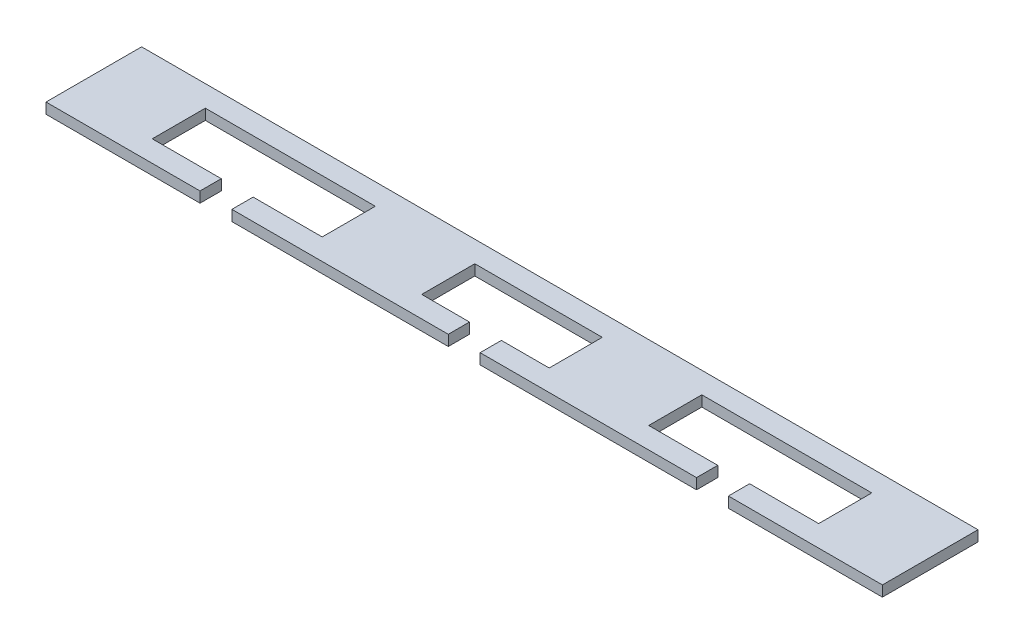
SolidWorks part; units mm, degrees
ref_plane "Front Plane" through (0, 0, 0) normal (0, 0, 1) x (1, 0, 0)
ref_plane "Top Plane" through (0, 0, 0) normal (0, 1, 0) x (1, 0, 0)
ref_plane "Right Plane" through (0, 0, 0) normal (1, 0, 0) x (0, 0, -1)
sketch "Sketch1" plane through (0, 0, 0) normal (0, 1, 0) x (1, 0, 0)
  line L0 (0, 57.15) -> (1000.0005, 57.15) construction
  line L2 (0, 0) -> (0, 114.3)
  line L3 (0, 114.3) -> (1000.0005, 114.3)
  line L4 (1000.0005, 0) -> (1000.0005, 114.3)
  line L9 (101.6, 25.4) -> (184.15, 25.4)
  line L10 (101.6, 25.4) -> (101.6, 88.9)
  line L12 (304.8, 25.4) -> (304.8, 88.9)
  line L17 (0, -31.5189) -> (406.4, -31.5189) construction
  line L18 (0, -31.5189) -> (0, -107.7189) construction
  line L19 (0, -107.7189) -> (406.4, -107.7189) construction
  line L20 (406.4, -31.5189) -> (406.4, -107.7189) construction
  line L21 (593.6005, -31.5189) -> (1000.0005, -31.5189) construction
  line L22 (593.6005, -31.5189) -> (593.6005, -107.7189) construction
  line L23 (593.6005, -107.7189) -> (1000.0005, -107.7189) construction
  line L24 (1000.0005, -31.5189) -> (1000.0005, -107.7189) construction
  line L25 (203.2, -31.5189) -> (203.2, -107.7189) construction
  line L26 (796.8005, -107.7189) -> (796.8005, -31.5189) construction
  line L27 (203.2, -31.5189) -> (203.2, 114.3) construction
  line L28 (796.8005, -31.5189) -> (796.8005, 114.3) construction
  line L29 (500.0003, -101.6) -> (500.0003, 114.3) construction
  line L30 (0, 0) -> (184.15, 0)
  line L35 (101.6, 88.9) -> (304.8, 88.9)
  line L36 (423.8003, 88.9) -> (576.2003, 88.9)
  line L37 (423.8003, 88.9) -> (423.8003, 25.4)
  line L38 (423.8003, 25.4) -> (480.9503, 25.4)
  line L39 (576.2003, 88.9) -> (576.2003, 25.4)
  line L40 (423.8003, 88.9) -> (576.2003, 25.4) construction
  line L41 (423.8003, 25.4) -> (576.2003, 88.9) construction
  line L42 (695.2005, 25.4) -> (695.2005, 88.9)
  line L43 (898.4005, 25.4) -> (815.8505, 25.4)
  line L44 (898.4005, 25.4) -> (898.4005, 88.9)
  line L45 (898.4005, 88.9) -> (695.2005, 88.9)
  line L46 (550.8003, 0) -> (777.7505, 0)
  line L48 (203.2, 12.7813) -> (184.15, 12.7813) construction
  line L49 (203.2, 12.7813) -> (222.25, 12.7813) construction
  line L50 (184.15, 25.4) -> (184.15, 0)
  line L51 (222.25, 25.4) -> (222.25, 0)
  line L52 (222.25, 25.4) -> (304.8, 25.4)
  line L53 (222.25, 0) -> (449.2003, 0)
  line L54 (796.8005, 12.7813) -> (777.7505, 12.7813) construction
  line L55 (796.8005, 12.7813) -> (815.8505, 12.7813) construction
  line L56 (777.7505, 25.4) -> (777.7505, 0)
  line L57 (815.8505, 25.4) -> (815.8505, 0)
  line L58 (815.8505, 0) -> (1000.0005, 0)
  line L59 (777.7505, 25.4) -> (695.2005, 25.4)
  line L60 (480.9503, 12.7813) -> (519.0503, 12.7813) construction
  line L61 (480.9503, 25.4) -> (480.9503, 0)
  line L62 (480.9503, 0) -> (449.2003, 0)
  line L63 (519.0503, 25.4) -> (519.0503, 0)
  line L64 (519.0503, 0) -> (550.8003, 0)
  line L65 (519.0503, 25.4) -> (576.2003, 25.4)
  point P36 (500.0003, 57.15)
  point P41 (101.6, 57.15)
  point P57 (500.0003, 12.7813)
  dimension "D1" = 406.4
  dimension "D2" = 76.2
  dimension "D3" = 1000.0005
  dimension "D6" = 203.2
  dimension "D7" = 38.1
  dimension "D8" = 19.05
  dimension "D9" = 19.05
  dimension "D10" = 152.4
  dimension "D11" = 63.5
  dimension "D12" = 25.4
  dimension "D13" = 25.4
  dimension "D14" = 184.15
  dimension "D15" = 101.6
  dimension "D16" = 38.1
extrude "Boss-Extrude1" add sketch "Sketch1" along normal blind 12.7
